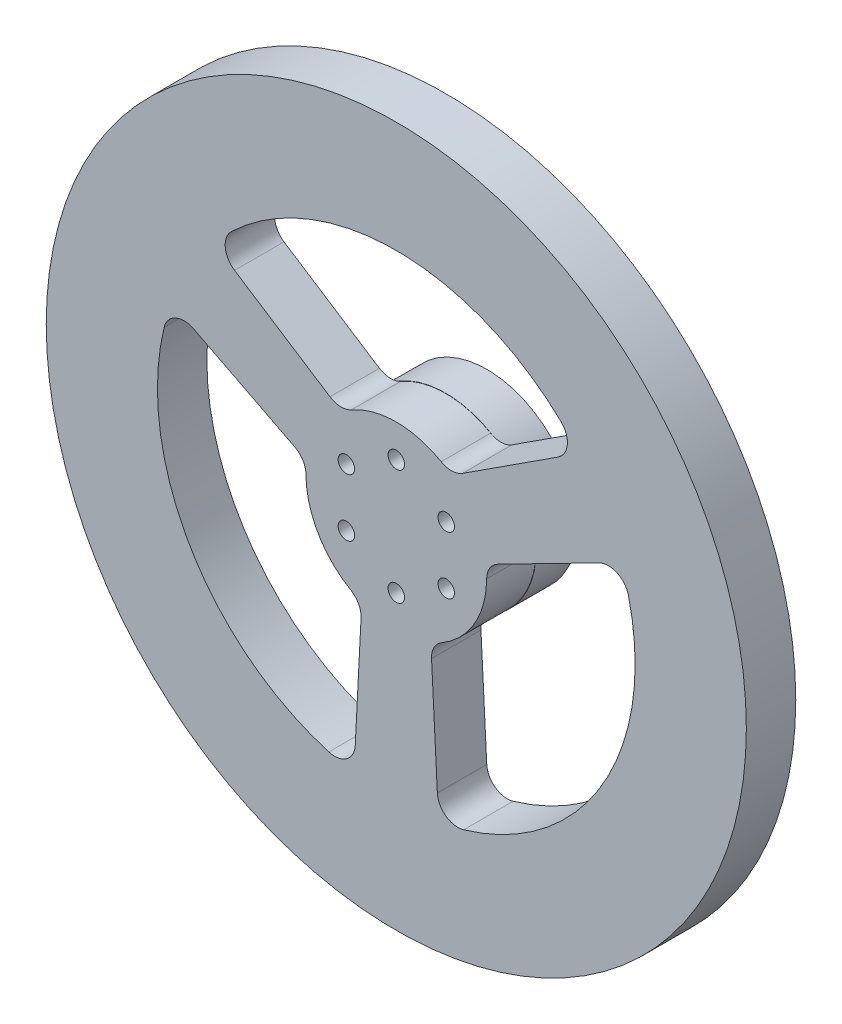
SolidWorks part; units mm, degrees
ref_plane "前视基准面" through (0, 0, 0) normal (0, 0, 1) x (1, 0, 0)
ref_plane "上视基准面" through (0, 0, 0) normal (0, 1, 0) x (1, 0, 0)
ref_plane "右视基准面" through (0, 0, 0) normal (1, 0, 0) x (0, 0, -1)
sketch "Sketch1" plane through (0, 0, 0) normal (0, 0, 1) x (1, 0, 0)
  line L0 (0, 0) -> (-73.6122, 42.5) construction
  line L1 (0, 0) -> (73.6122, 42.5) construction
  line L2 (73.6122, 42.5) -> (-73.6122, 42.5) construction
  line L3 (0, 85) -> (0, -85) construction
  line L10 (-16.1048, 19.1791) -> (-39.27, 34.1824)
  line L11 (16.1048, 19.1791) -> (39.27, 34.1824)
  line L12 (8.5572, -23.5367) -> (9.9678, -51.1)
  line L13 (24.662, 4.3576) -> (49.2378, 16.9176)
  line L14 (-24.662, 4.3576) -> (-49.2378, 16.9176)
  line L15 (-8.5572, -23.5367) -> (-9.9678, -51.1)
  line L16 (-39.27, 34.1824) -> (-73.6122, 42.5) construction
  line L17 (39.27, 34.1824) -> (73.6122, 42.5) construction
  circle A0 centre (0, 0) radius 85
  circle A2 centre (0, 14) radius 2
  circle A3 centre (12.1244, 7) radius 2
  circle A4 centre (12.1244, -7) radius 2
  circle A5 centre (0, -14) radius 2
  circle A6 centre (-12.1244, -7) radius 2
  circle A7 centre (-12.1244, 7) radius 2
  circle A8 centre (0, 0) radius 16
  circle A9 centre (0, 0) radius 24
  arc A28 (-40.0002, 41.9998) -> (40.0002, 41.9998) centre (0, 0) cw
  arc A29 (-10.902, 19.0369) -> (10.902, 19.0369) centre (0, 0) cw
  arc A30 (40.0002, 41.9998) -> (39.27, 34.1824) centre (36.5519, 38.3791) cw
  arc A31 (10.902, 19.0369) -> (16.1048, 19.1791) centre (13.3867, 23.3758) ccw
  arc A32 (-10.902, 19.0369) -> (-16.1048, 19.1791) centre (-13.3867, 23.3758) cw
  arc A33 (-40.0002, 41.9998) -> (-39.27, 34.1824) centre (-36.5519, 38.3791) ccw
  arc A34 (11.0355, -18.9598) -> (8.5572, -23.5367) centre (13.5507, -23.2811) ccw
  arc A35 (16.3727, -55.6411) -> (9.9678, -51.1) centre (14.9613, -50.8445) cw
  arc A36 (56.373, 13.6413) -> (16.3727, -55.6411) centre (0, 0) cw
  arc A37 (56.373, 13.6413) -> (49.2378, 16.9176) centre (51.5132, 12.4654) ccw
  arc A38 (21.9374, -0.0771) -> (24.662, 4.3576) centre (26.9374, -0.0947) cw
  arc A39 (21.9374, -0.0771) -> (11.0355, -18.9598) centre (0, 0) cw
  arc A40 (-21.9374, -0.0771) -> (-24.662, 4.3576) centre (-26.9374, -0.0947) ccw
  arc A41 (-56.373, 13.6413) -> (-49.2378, 16.9176) centre (-51.5132, 12.4654) cw
  arc A42 (-16.3727, -55.6411) -> (-56.373, 13.6413) centre (0, 0) cw
  arc A43 (-16.3727, -55.6411) -> (-9.9678, -51.1) centre (-14.9613, -50.8445) ccw
  arc A44 (-11.0355, -18.9598) -> (-8.5572, -23.5367) centre (-13.5507, -23.2811) cw
  arc A45 (-11.0355, -18.9598) -> (-21.9374, -0.0771) centre (0, 0) cw
  point P7 (0, 42.5)
  point P19 (0, 0)
  point P32 (13.3591, 17.4009)
  point P35 (-13.3591, 17.4009)
  point P43 (0, 0)
  point P65 (0, 0)
  dimension "D1" = 170
  dimension "D2" = 8
  dimension "D3" = 4
  dimension "D6" = 5
  dimension "D7" = 3
  dimension "D5" = 120
  dimension "D4" = 6
extrude "Boss-Extrude1" add sketch "Sketch1" along normal blind 12
sketch "Sketch3" plane through (0, 0, 0) normal (0, 0, -1) x (-1, 0, 0)
  circle A0 centre (0, 0) radius 22
extrude "Boss-Extrude2" add sketch "Sketch3" along normal blind 10
sketch "Sketch5" plane through (0, 0, 12) normal (0, 0, 1) x (1, 0, 0)
  circle A0 centre (0, 14) radius 2
  circle A1 centre (12.1244, 7) radius 2
  circle A2 centre (12.1244, -7) radius 2
  circle A3 centre (0, -14) radius 2
  circle A4 centre (-12.1244, -7) radius 2
  circle A5 centre (-12.1244, 7) radius 2
extrude "Cut-Extrude1" cut sketch "Sketch5" against normal through all both and the other way through all
